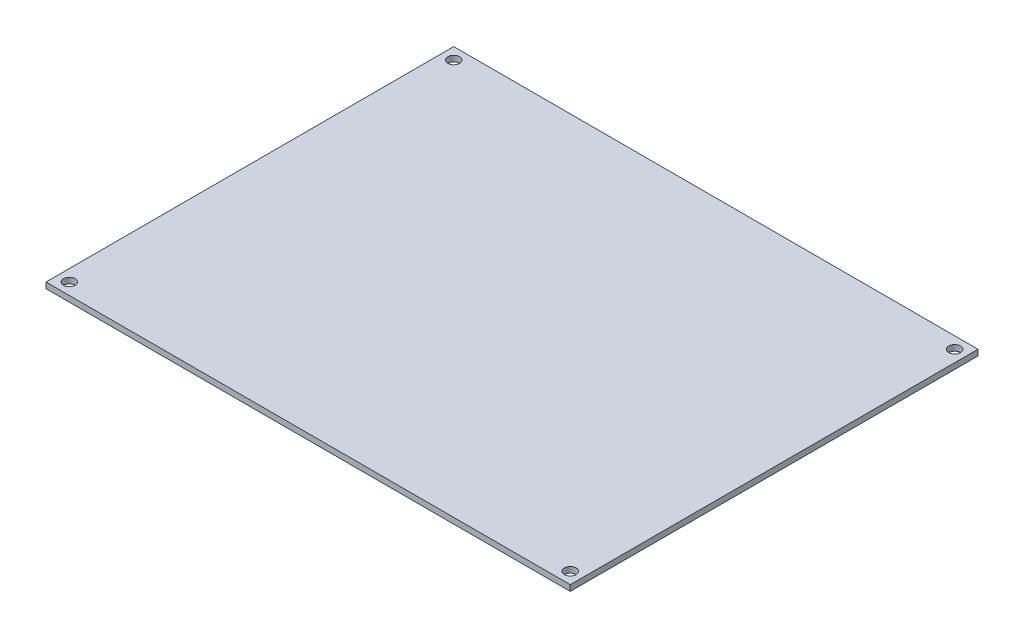
SolidWorks part; units mm, degrees
ref_plane "Front Plane" through (0, 0, 0) normal (0, 0, 1) x (1, 0, 0)
ref_plane "Top Plane" through (0, 0, 0) normal (0, 1, 0) x (1, 0, 0)
ref_plane "Right Plane" through (0, 0, 0) normal (1, 0, 0) x (0, 0, -1)
sketch "Sketch1" plane through (0, 0, 0) normal (0, 1, 0) x (1, 0, 0)
  line L1 (0, 0) -> (90, 0)
  line L2 (0, 0) -> (0, 70)
  line L3 (0, 70) -> (90, 70)
  line L4 (90, 0) -> (90, 70)
  dimension "D1" = 90
  dimension "D2" = 70
extrude "Boss-Extrude1" add sketch "Sketch1" along normal blind 1
sketch "Sketch2" plane through (0, 1, 0) normal (0, 1, 0) x (1, 0, 0)
  line L0 (0, 70) -> (90, 0) construction
  line L2 (2, 2) -> (88, 2) construction
  line L3 (2, 2) -> (2, 68) construction
  line L4 (2, 68) -> (88, 68) construction
  line L5 (88, 2) -> (88, 68) construction
  line L6 (2, 2) -> (88, 68) construction
  line L7 (2, 68) -> (88, 2) construction
  circle A0 centre (88, 68) radius 1
  circle A1 centre (88, 2) radius 1
  circle A2 centre (2, 2) radius 1
  circle A3 centre (2, 68) radius 1
  point P4 (45, 35)
  point P14 (0, 0)
  point P15 (45.345, 35.414)
  point P16 (0, 0)
  dimension "D1" = 2
  dimension "D2" = 66
  dimension "D3" = 86
extrude "Cut-Extrude1" cut sketch "Sketch2" against normal blind 10
